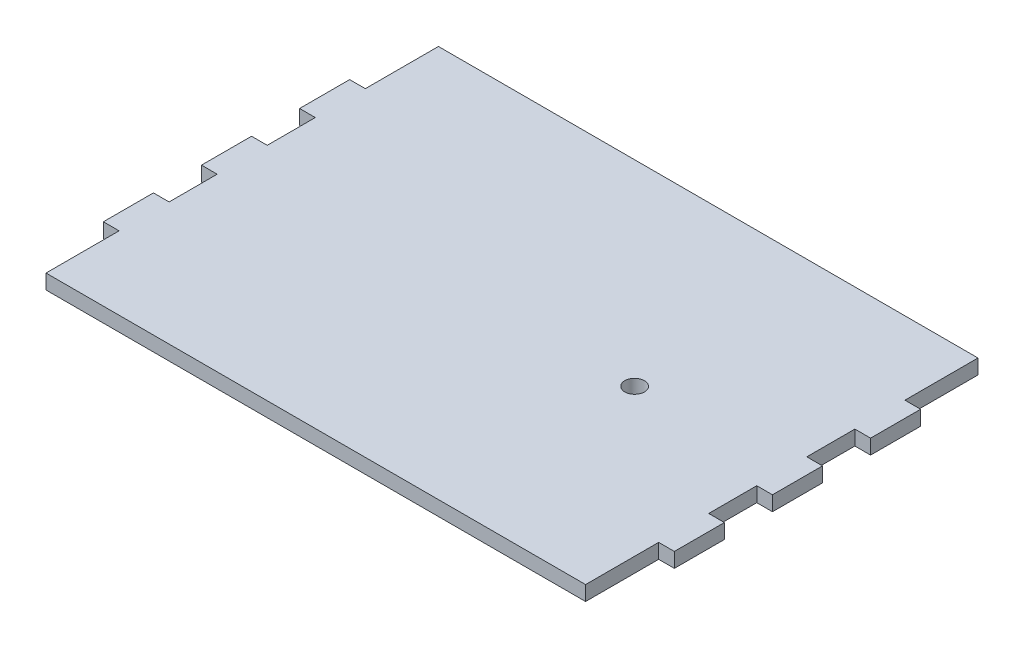
SolidWorks part; units mm, degrees
ref_plane "Alzado" through (0, 0, 0) normal (0, 0, 1) x (1, 0, 0)
ref_plane "Planta" through (0, 0, 0) normal (0, 1, 0) x (1, 0, 0)
ref_plane "Vista lateral" through (0, 0, 0) normal (1, 0, 0) x (0, 0, -1)
sketch "Croquis1" plane through (0, 0, 0) normal (0, 1, 0) x (1, 0, 0)
  line L0 (55, 14.9) -> (55, 5.1)
  line L1 (-55, 40) -> (55, 40)
  line L2 (-55, 40) -> (-55, 25.1)
  line L3 (-55, -40) -> (55, -40)
  line L4 (55, 40) -> (55, 25.1)
  line L5 (-55, 40) -> (55, -40) construction
  line L6 (-55, -40) -> (55, 40) construction
  line L7 (55, 25.1) -> (58.2, 25.1)
  line L9 (55, 14.9) -> (58.2, 14.9)
  line L10 (58.2, 25.1) -> (58.2, 14.9)
  line L11 (55, 5.1) -> (58.2, 5.1)
  line L13 (55, -5.1) -> (58.2, -5.1)
  line L14 (58.2, 5.1) -> (58.2, -5.1)
  line L15 (55, -5.1) -> (55, -14.9)
  line L16 (0, 0) -> (7.7214, 0) construction
  line L17 (55, -25.1) -> (58.2, -25.1)
  line L18 (55, -14.9) -> (58.2, -14.9)
  line L19 (58.2, -25.1) -> (58.2, -14.9)
  line L20 (55, -25.1) -> (55, -40)
  line L21 (0, 0) -> (0, -18.9088) construction
  line L22 (-58.2, -25.1) -> (-58.2, -14.9)
  line L23 (-55, -25.1) -> (-58.2, -25.1)
  line L24 (-55, -14.9) -> (-58.2, -14.9)
  line L25 (-58.2, 5.1) -> (-58.2, -5.1)
  line L26 (-55, -5.1) -> (-58.2, -5.1)
  line L27 (-55, 5.1) -> (-58.2, 5.1)
  line L28 (-58.2, 25.1) -> (-58.2, 14.9)
  line L29 (-55, 14.9) -> (-58.2, 14.9)
  line L30 (-55, 25.1) -> (-58.2, 25.1)
  line L31 (-55, 14.9) -> (-55, 5.1)
  line L32 (-55, -5.1) -> (-55, -14.9)
  line L33 (-55, -25.1) -> (-55, -40)
  circle A1 centre (25, 0) radius 2
  point P0 (0, 0)
  point P10 (58.2, 20)
  point P15 (58.2, 0)
  dimension "D9" = 4
  dimension "D1" = 80
  dimension "D2" = 110
  dimension "D3" = 3.2
  dimension "D4" = 10.2
  dimension "D5" = 20
  dimension "D6" = 3.2
  dimension "D7" = 10.2
  dimension "D8" = 20
  dimension "D10" = 30
  dimension "D11" = 40
extrude "Saliente-Extruir1" add sketch "Croquis1" along normal blind 3
